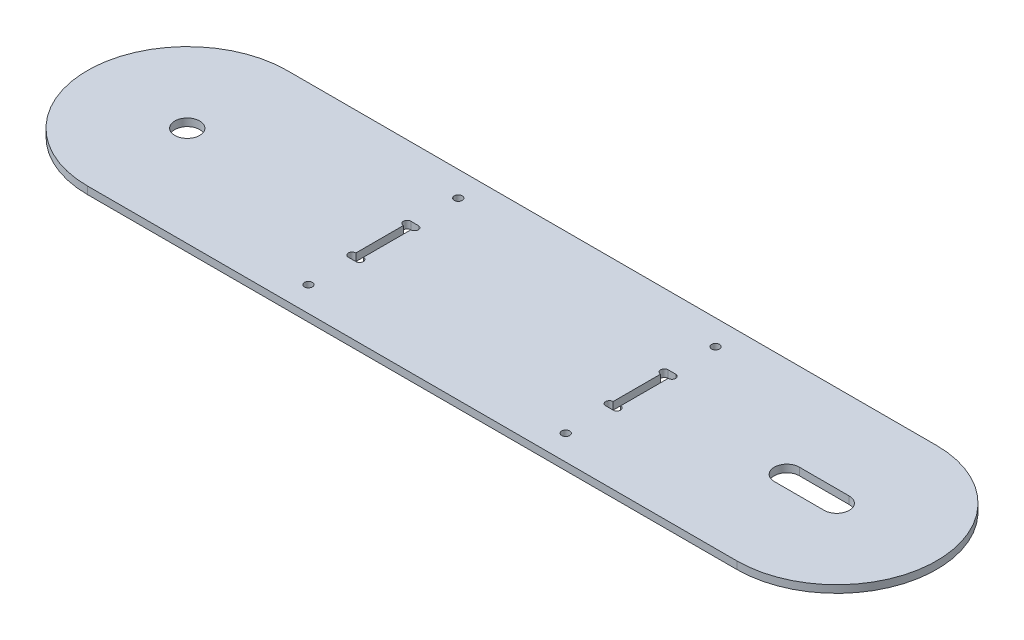
SolidWorks part; units mm, degrees
ref_plane "Front Plane" through (0, 0, 0) normal (0, 0, 1) x (1, 0, 0)
ref_plane "Top Plane" through (0, 0, 0) normal (0, 1, 0) x (1, 0, 0)
ref_plane "Right Plane" through (0, 0, 0) normal (1, 0, 0) x (0, 0, -1)
sketch "Sketch1" plane through (0, 0, 0) normal (0, 1, 0) x (1, 0, 0)
  line L0 (0, 0) -> (260, 0) construction
  line L5 (0, 40) -> (260, 40)
  line L6 (0, -40) -> (260, -40)
  line L7 (260, 0) -> (240, 0) construction
  line L8 (260, -5) -> (240, -5)
  line L9 (260, 5) -> (240, 5)
  arc A0 (0, 40) -> (0, -40) centre (0, 0) ccw
  arc A1 (260, -40) -> (260, 40) centre (260, 0) ccw
  circle A2 centre (0, 0) radius 5
  arc A4 (260, -5) -> (260, 5) centre (260, 0) ccw
  arc A5 (240, 5) -> (240, -5) centre (240, 0) ccw
  point P2 (130, 0)
  point P12 (250, 0)
  dimension "D2" = 40
  dimension "D3" = 10
  dimension "D1" = 260
  dimension "D4" = 20
extrude "Boss-Extrude1" add sketch "Sketch1" along normal blind 3
sketch "Sketch2" plane through (0, 3, 0) normal (0, 1, 0) x (1, 0, 0)
  line L0 (-40, 0) -> (300, 0) construction
  line L1 (130, 40) -> (130, -40) construction
  line L5 (80, 9.5) -> (80, -9.5)
  line L6 (260, 40) -> (0, 40) construction
  line L7 (0, -40) -> (260, -40) construction
  line L8 (77, 11) -> (80, 11) construction
  line L9 (77, 12.5) -> (80, 12.5)
  line L11 (77, -11) -> (80, -11) construction
  line L13 (77, -12.5) -> (80, -12.5)
  line L14 (77, 9.5) -> (77, -9.5)
  line L15 (183, 12.5) -> (180, 12.5)
  line L16 (183, 9.5) -> (183, -9.5)
  line L17 (183, -12.5) -> (180, -12.5)
  line L18 (180, 9.5) -> (180, -9.5)
  line L19 (78.5, 40) -> (78.5, -40) construction
  arc A0 (0, 40) -> (0, -40) centre (0, 0) ccw construction
  arc A1 (260, -40) -> (260, 40) centre (260, 0) ccw construction
  arc A2 (77, 12.5) -> (77, 9.5) centre (77, 11) ccw
  arc A3 (80, 9.5) -> (80, 12.5) centre (80, 11) ccw
  arc A4 (77, -9.5) -> (77, -12.5) centre (77, -11) ccw
  arc A5 (80, -12.5) -> (80, -9.5) centre (80, -11) ccw
  arc A6 (180, 9.5) -> (180, 12.5) centre (180, 11) cw
  arc A7 (183, 12.5) -> (183, 9.5) centre (183, 11) cw
  arc A8 (183, -9.5) -> (183, -12.5) centre (183, -11) cw
  arc A9 (180, -12.5) -> (180, -9.5) centre (180, -11) cw
  circle A10 centre (78.5, 30) radius 1.6
  circle A11 centre (78.5, -30) radius 1.6
  circle A12 centre (181.5, -30) radius 1.6
  circle A13 centre (181.5, 30) radius 1.6
  point P9 (78.5, 11)
  point P11 (77, 0)
  dimension "D2" = 1.5
  dimension "D3" = 1.5
  dimension "D6" = 3.2
  dimension "D1" = 3
  dimension "D4" = 25
  dimension "D5" = 50
  dimension "D7" = 10
  dimension "D8" = 10
extrude "Cut-Extrude1" cut sketch "Sketch2" against normal through all
